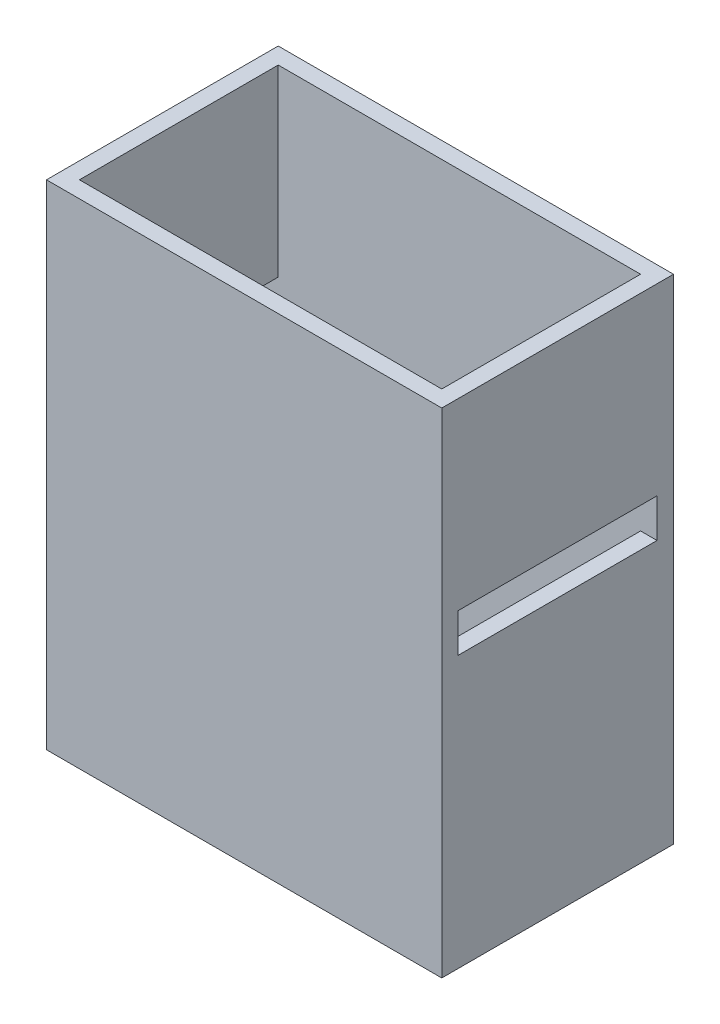
SolidWorks part; units mm, degrees
ref_plane "Front Plane" through (0, 0, 0) normal (0, 0, 1) x (1, 0, 0)
ref_plane "Top Plane" through (0, 0, 0) normal (0, 1, 0) x (1, 0, 0)
ref_plane "Right Plane" through (0, 0, 0) normal (1, 0, 0) x (0, 0, -1)
sketch "Sketch1" plane through (0, 0, 0) normal (0, 1, 0) x (1, 0, 0)
  line L1 (0, 0) -> (24, 0)
  line L2 (0, 0) -> (0, 14.07)
  line L3 (0, 14.07) -> (24, 14.07)
  line L4 (24, 0) -> (24, 14.07)
  dimension "D1" = 24
  dimension "D2" = 14.07
extrude "Boss-Extrude1" add sketch "Sketch1" along normal blind 29.97
sketch "Sketch2" plane through (0, 29.97, 0) normal (0, 1, 0) x (1, 0, 0)
  line L0 (1, 14.07) -> (1, 13.07) construction
  line L1 (24, 14.07) -> (0, 14.07) construction
  line L2 (1, 13.07) -> (0, 13.07) construction
  line L3 (0, 14.07) -> (0, 0) construction
  line L4 (0, 1) -> (1, 1) construction
  line L5 (1, 1) -> (1, 0) construction
  line L6 (0, 0) -> (24, 0) construction
  line L7 (24, 1) -> (23, 1) construction
  line L8 (24, 0) -> (24, 14.07) construction
  line L9 (23, 1) -> (23, 0) construction
  line L10 (23, 14.07) -> (23, 13.07) construction
  line L11 (23, 13.07) -> (24, 13.07) construction
  line L12 (1, 13.07) -> (1, 1)
  line L13 (1, 1) -> (23, 1)
  line L14 (23, 1) -> (23, 13.07)
  line L15 (23, 13.07) -> (1, 13.07)
  dimension "D1" = 1
  dimension "D2" = 1
  dimension "D3" = 1
  dimension "D4" = 1
  dimension "D5" = 1
  dimension "D6" = 1
  dimension "D7" = 1
  dimension "D8" = 1
extrude "Cut-Extrude1" cut sketch "Sketch2" against normal blind 28.97
sketch "Sketch3" plane through (0, 0, 0) normal (-1, 0, 0) x (0, 0, 1)
  line L0 (-14.07, 29.97) -> (-14.07, 18.82) construction
  line L1 (-14.07, 29.97) -> (-14.07, 0) construction
  line L2 (-14.07, 18.82) -> (-13.07, 18.82) construction
  line L3 (0, 18.82) -> (-1, 18.82) construction
  line L4 (0, 29.97) -> (0, 0) construction
  line L5 (-13.07, 18.82) -> (-1, 18.82)
  line L6 (-1, 18.82) -> (-1, 16.47)
  line L7 (-1, 16.47) -> (-13.07, 16.47)
  line L8 (-13.07, 16.47) -> (-13.07, 18.82)
  dimension "D1" = 11.15
  dimension "D2" = 1
  dimension "D3" = 1
  dimension "D4" = 2.35
extrude "Cut-Extrude2" cut sketch "Sketch3" against normal through all both and the other way through all
